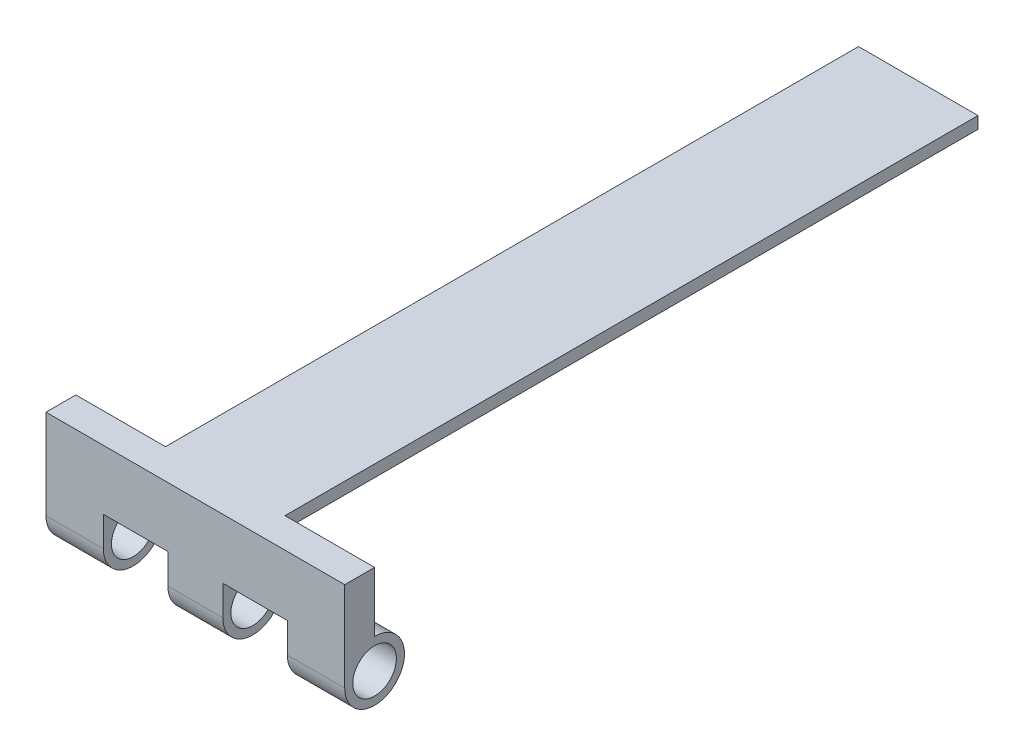
SolidWorks part; units mm, degrees
ref_plane "Front Plane" through (0, 0, 0) normal (0, 0, 1) x (1, 0, 0)
ref_plane "Top Plane" through (0, 0, 0) normal (0, 1, 0) x (1, 0, 0)
ref_plane "Right Plane" through (0, 0, 0) normal (1, 0, 0) x (0, 0, -1)
sketch "Sketch1" plane through (0, 0, 0) normal (1, 0, 0) x (0, 0, -1)
  line L1 (0, 0) -> (-6.35, 0)
  line L2 (0, 0) -> (0, 19.05)
  line L3 (0, 19.05) -> (-6.35, 19.05)
  line L4 (-6.35, 0) -> (-6.35, 19.05)
  dimension "D1" = 6.35
  dimension "D2" = 19.05
extrude "Boss-Extrude1" add sketch "Sketch1" along normal mid plane 63.5
sketch "Sketch2" plane through (0, 0, 0) normal (1, 0, 0) x (0, 0, -1)
  line L0 (0, 19.05) -> (147.32, 19.05)
  line L3 (0, 0) -> (0, 19.05) construction
  dimension "D2" = 147.32
extrude "Extrude-Thin1" add sketch "Sketch2" along normal mid plane 25.4 thin
sketch "Sketch3" plane through (31.75, 0, 0) normal (1, 0, 0) x (0, 0, -1)
  circle A0 centre (0, 0) radius 6.35
sweep "Sweep1" add profiles "Sketch3" path edge at (0, 0, 0)
sketch "Sketch4" plane through (31.75, 0, 0) normal (1, 0, 0) x (0, 0, -1)
  circle A0 centre (0, 0) radius 4.6355
  dimension "D1" = 9.271
extrude "Cut-Extrude2" cut sketch "Sketch4" against normal through all
sketch "Sketch5" plane through (0, 0, 6.35) normal (0, 0, 1) x (1, 0, 0)
  line L0 (0, -23.3084) -> (0, 29.6429) construction
  line L1 (-31.75, -6.35) -> (31.75, -6.35) construction
  line L2 (5.842, 6.35) -> (19.558, 6.35)
  line L3 (5.842, 6.35) -> (5.842, -6.35)
  line L4 (5.842, -6.35) -> (19.558, -6.35)
  line L5 (19.558, 6.35) -> (19.558, -6.35)
  line L6 (-31.75, -6.35) -> (31.75, -6.35) construction
  line L7 (-19.558, 6.35) -> (-5.842, 6.35)
  line L8 (-19.558, 6.35) -> (-19.558, -6.35)
  line L9 (-19.558, -6.35) -> (-5.842, -6.35)
  line L10 (-5.842, 6.35) -> (-5.842, -6.35)
  dimension "D1" = 13.716
  dimension "D2" = 12.7
  dimension "D3" = 5.842
  dimension "D4" = 13.716
  dimension "D5" = 5.842
extrude "Cut-Extrude4" cut sketch "Sketch5" against normal through all both and the other way through all
